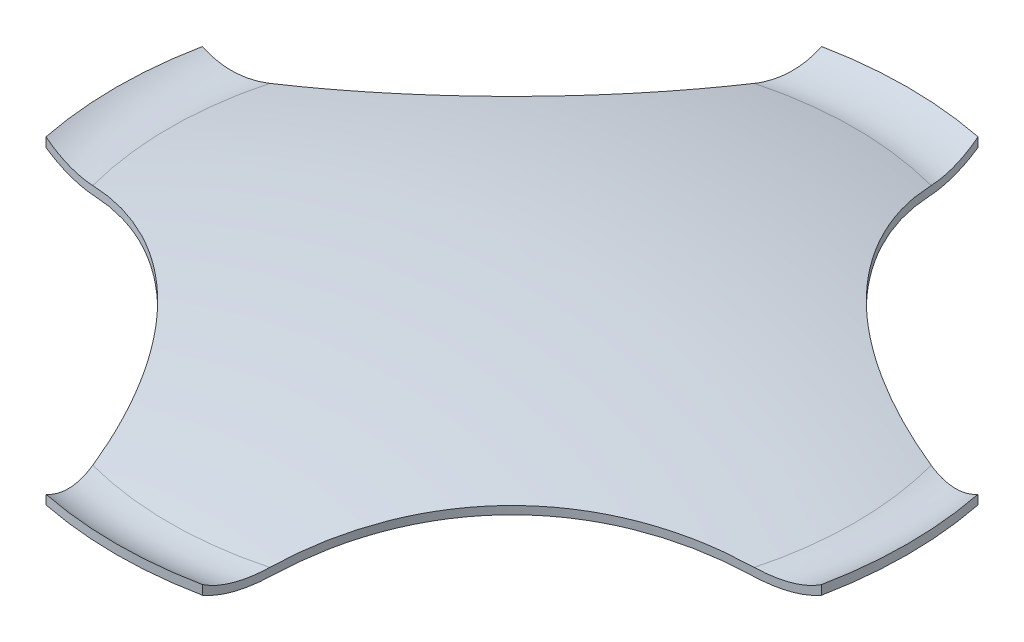
SolidWorks part; units mm, degrees
ref_plane "Front Plane" through (0, 0, 0) normal (0, 0, 1) x (1, 0, 0)
ref_plane "Top Plane" through (0, 0, 0) normal (0, 1, 0) x (1, 0, 0)
ref_plane "Right Plane" through (0, 0, 0) normal (1, 0, 0) x (0, 0, -1)
ref_axis "Axis1" through (0, -0.9074, 0) along (0, 1, 0)
sketch "Sketch2" plane through (0, 0, 0) normal (0, 1, 0) x (1, 0, 0)
  line L0 (0, 3) -> (0, -3) construction
  line L1 (-3, 0) -> (3, 0) construction
  line L2 (2.1213, 2.1213) -> (-2.1213, -2.1213) construction
  line L3 (-2.1213, 2.1213) -> (2.1213, -2.1213) construction
  circle A0 centre (0, 0) radius 3
  arc A1 (0.5932, 2.9408) -> (2.9408, 0.5932) centre (3.182, 3.182) ccw
  arc A2 (-2.9408, -0.5932) -> (-0.5932, -2.9408) centre (-3.182, -3.182) cw
  arc A3 (-2.9408, 0.5932) -> (-0.5932, 2.9408) centre (-3.182, 3.182) ccw
  arc A4 (0.5932, -2.9408) -> (2.9408, -0.5932) centre (3.182, -3.182) cw
  dimension "D1" = 6
  dimension "D2" = 2.6
  dimension "D3" = 3.8
sketch "Sketch3" plane through (0, 0, 0) normal (0, 0, 1) x (1, 0, 0)
  line L0 (3, 0.0717) -> (3, 0.1418)
  line L1 (0, 0.36) -> (0, 0.42)
  line L2 (-3, 0) -> (3, 0) construction
  arc A0 (0, 0.42) -> (2.5961, 0.0771) centre (0, -9.58) cw
  arc A1 (2.5961, 0.0771) -> (3, 0.1418) centre (2.7259, 0.56) ccw
  arc A2 (3, 0.0717) -> (2.5805, 0.0192) centre (2.7259, 0.56) cw
  arc A3 (2.5805, 0.0192) -> (0, 0.36) centre (0, -9.58) ccw
  point P19 (2.7259, 0)
  dimension "D1" = 0.06
  dimension "D4" = 10
  dimension "D3" = 0.5
  dimension "D2" = 0.42
sketch "Sketch5" plane through (0, 0, 0) normal (0, 0, 1) x (1, 0, 0)
  line L0 (0, 0.36) -> (0, 0.42) construction
  line L1 (3, 0.0717) -> (3, 0.1418) construction
  line L2 (0, 0.36) -> (0, 0.42)
  line L3 (3, 0.0717) -> (3, 0.1418)
  arc A0 (2.5805, 0.0192) -> (0, 0.36) centre (0, -9.58) ccw construction
  arc A1 (2.5805, 0.0192) -> (3, 0.0717) centre (2.7259, 0.56) ccw construction
  arc A2 (2.5961, 0.0771) -> (3, 0.1418) centre (2.7259, 0.56) ccw construction
  arc A3 (2.5961, 0.0771) -> (0, 0.42) centre (0, -9.58) ccw construction
  arc A4 (2.5805, 0.0192) -> (0, 0.36) centre (0, -9.58) ccw
  arc A5 (2.5805, 0.0192) -> (3, 0.0717) centre (2.7259, 0.56) ccw
  arc A6 (2.5961, 0.0771) -> (3, 0.1418) centre (2.7259, 0.56) ccw
  arc A7 (2.5961, 0.0771) -> (0, 0.42) centre (0, -9.58) ccw
revolve "Revolve1" add sketch "Sketch5" angle 360 about axis through (0, -0.9074, 0) along (0, 1, 0)
sketch "Sketch6" plane through (0, 0, 0) normal (0, 1, 0) x (1, 0, 0)
  arc A0 (0.5932, 2.9408) -> (2.9408, 0.5932) centre (3.182, 3.182) ccw construction
  arc A1 (0.5932, 2.9408) -> (2.9408, 0.5932) centre (3.182, 3.182) ccw
  arc A2 (2.9408, -0.5932) -> (0.5932, -2.9408) centre (3.182, -3.182) ccw construction
  arc A3 (2.9408, -0.5932) -> (0.5932, -2.9408) centre (3.182, -3.182) ccw
  arc A4 (-0.5932, -2.9408) -> (-2.9408, -0.5932) centre (-3.182, -3.182) ccw construction
  arc A5 (-0.5932, -2.9408) -> (-2.9408, -0.5932) centre (-3.182, -3.182) ccw
  arc A6 (-2.9408, 0.5932) -> (-0.5932, 2.9408) centre (-3.182, 3.182) ccw construction
  arc A7 (-2.9408, 0.5932) -> (-0.5932, 2.9408) centre (-3.182, 3.182) ccw
  circle A8 centre (0, 0) radius 3 construction
  arc A9 (-2.9408, -0.5932) -> (-0.5932, -2.9408) centre (0, 0) ccw
  arc A10 (-0.5932, 2.9408) -> (-2.9408, 0.5932) centre (0, 0) ccw
  arc A11 (2.9408, 0.5932) -> (0.5932, 2.9408) centre (0, 0) ccw
  arc A12 (0.5932, -2.9408) -> (2.9408, -0.5932) centre (0, 0) ccw
extrude "Cut-Extrude1" cut sketch "Sketch6" along normal through all
